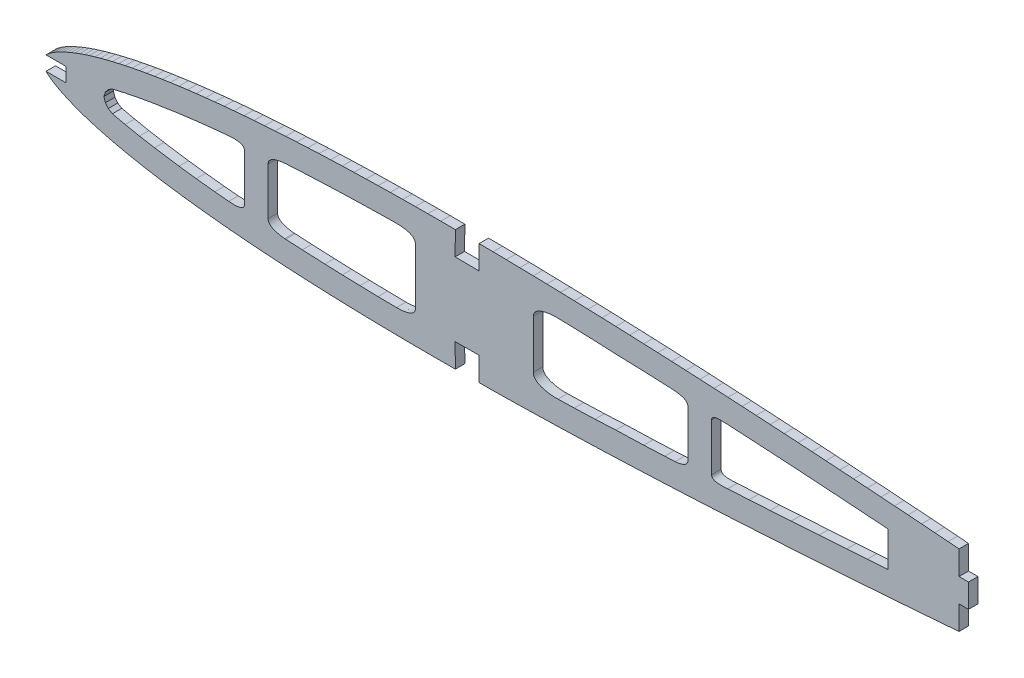
SolidWorks part; units mm, degrees
ref_plane "前视基准面" through (0, 0, 0) normal (0, 0, 1) x (1, 0, 0)
ref_plane "上视基准面" through (0, 0, 0) normal (0, 1, 0) x (1, 0, 0)
ref_plane "右视基准面" through (0, 0, 0) normal (1, 0, 0) x (0, 0, -1)
sketch "Model" plane through (0, 0, 0) normal (0, 0, 1) x (1, 0, 0)
  line L0 (191.5152, 23.6015) -> (189.1892, 23.7857)
  line L1 (189.1892, 23.7857) -> (186.3982, 24.0037)
  line L2 (186.3982, 24.0037) -> (183.6072, 24.2187)
  line L3 (183.6072, 24.2187) -> (180.7582, 24.4357)
  line L4 (180.7582, 24.4357) -> (177.9092, 24.6477)
  line L5 (177.9092, 24.6477) -> (175.0602, 24.8567)
  line L6 (175.0602, 24.8567) -> (172.1632, 25.0647)
  line L7 (172.1632, 25.0647) -> (169.2682, 25.2687)
  line L8 (169.2682, 25.2687) -> (166.3712, 25.4687)
  line L9 (166.3712, 25.4687) -> (163.4412, 25.6677)
  line L10 (163.4412, 25.6677) -> (160.5112, 25.8627)
  line L11 (160.5112, 25.8627) -> (157.5802, 26.0527)
  line L12 (157.5802, 26.0527) -> (154.6252, 26.2367)
  line L13 (154.6252, 26.2367) -> (151.6712, 26.4157)
  line L14 (151.6712, 26.4157) -> (148.7162, 26.5907)
  line L15 (148.7162, 26.5907) -> (145.7502, 26.7647)
  line L16 (145.7502, 26.7647) -> (142.7862, 26.9337)
  line L17 (142.7862, 26.9337) -> (139.8202, 27.0977)
  line L18 (139.8202, 27.0977) -> (136.8552, 27.2557)
  line L19 (136.8552, 27.2557) -> (133.8902, 27.4057)
  line L20 (133.8902, 27.4057) -> (130.9242, 27.5487)
  line L21 (130.9242, 27.5487) -> (127.9702, 27.6847)
  line L22 (127.9702, 27.6847) -> (125.0152, 27.8137)
  line L23 (125.0152, 27.8137) -> (122.0602, 27.9367)
  line L24 (122.0602, 27.9367) -> (119.1302, 28.0527)
  line L25 (119.1302, 28.0527) -> (116.2002, 28.1617)
  line L26 (116.2002, 28.1617) -> (113.2692, 28.2627)
  line L27 (113.2692, 28.2627) -> (110.3732, 28.3557)
  line L28 (110.3732, 28.3557) -> (107.4772, 28.4407)
  line L29 (107.4772, 28.4407) -> (104.5802, 28.5177)
  line L30 (104.5802, 28.5177) -> (101.7312, 28.5867)
  line L31 (101.7312, 28.5867) -> (98.8832, 28.6477)
  line L32 (98.8832, 28.6477) -> (96.0332, 28.6997)
  line L33 (96.0332, 28.6997) -> (93.2422, 28.7417)
  line L34 (93.2422, 28.7417) -> (90.2887, 28.7567)
  line L35 (12.9542, 18.3227) -> (15.6532, 18.9327)
  line L36 (15.6532, 18.9327) -> (18.6702, 19.5337)
  line L37 (18.6702, 19.5337) -> (21.8492, 20.0927)
  line L38 (21.8492, 20.0927) -> (27.0022, 20.8667)
  line L39 (27.0022, 20.8667) -> (30.6412, 21.3307)
  line L40 (30.6412, 21.3307) -> (34.5652, 21.7657)
  line L41 (34.5652, 21.7657) -> (37.7693, 22.0681)
  line L42 (49.5012, 22.9567) -> (53.0172, 23.1467)
  line L43 (53.0172, 23.1467) -> (57.193, 23.3345)
  line L44 (59.6022, 23.4284) -> (61.4422, 23.4967)
  line L45 (61.4422, 23.4967) -> (65.1737, 23.6052)
  line L46 (65.1737, 23.6052) -> (69.0032, 23.6947)
  line L47 (69.0032, 23.6947) -> (72.3897, 23.7484)
  line L48 (72.8792, 8.3632) -> (69.0032, 8.4247)
  line L49 (69.0032, 8.4247) -> (65.1737, 8.5142)
  line L50 (65.1737, 8.5142) -> (61.4422, 8.6227)
  line L51 (61.4422, 8.6227) -> (57.7622, 8.7592)
  line L52 (57.7622, 8.7592) -> (53.0172, 8.9727)
  line L53 (53.0172, 8.9727) -> (49.5012, 9.1627)
  line L54 (49.5012, 9.1627) -> (49.2998, 9.1756)
  line L55 (37.4946, 10.0771) -> (34.5652, 10.3537)
  line L56 (34.5652, 10.3537) -> (30.6412, 10.7887)
  line L57 (30.6412, 10.7887) -> (27.0022, 11.2527)
  line L58 (27.0022, 11.2527) -> (21.8492, 12.0267)
  line L59 (21.8492, 12.0267) -> (18.6702, 12.5857)
  line L60 (18.6702, 12.5857) -> (15.6532, 13.1867)
  line L61 (15.6532, 13.1867) -> (12.9542, 13.7967)
  line L62 (12.9542, 18.3227) -> (12.0865, 17.8016)
  line L63 (12.0865, 17.8016) -> (11.4898, 17.0319)
  line L64 (11.4898, 17.0319) -> (11.1665, 16.0597)
  line L65 (12.9542, 13.7967) -> (12.0865, 14.3178)
  line L66 (12.0865, 14.3178) -> (11.4898, 15.0874)
  line L67 (11.4898, 15.0874) -> (11.1665, 16.0597)
  line L68 (106.8793, 23.455) -> (110.3732, 23.3557)
  line L69 (110.3732, 23.3557) -> (113.5776, 23.2502)
  line L70 (116.1585, 23.1417) -> (119.1302, 22.9947)
  line L71 (119.1302, 22.9947) -> (125.0152, 22.8137)
  line L72 (125.0152, 22.8137) -> (129.4472, 22.6167)
  line L73 (129.4472, 22.6167) -> (131.1657, 22.5337)
  line L74 (142.5984, 21.9418) -> (147.2332, 21.6777)
  line L75 (147.2332, 21.6777) -> (151.6712, 21.4157)
  line L76 (151.6712, 21.4157) -> (156.1027, 21.1447)
  line L77 (156.1027, 21.1447) -> (161.9762, 20.7652)
  line L78 (161.9762, 20.7652) -> (167.8197, 20.3687)
  line L79 (167.8197, 20.3687) -> (172.1632, 20.0647)
  line L80 (172.1632, 20.0647) -> (176.4847, 19.7522)
  line L81 (176.4847, 12.3672) -> (172.1632, 12.0547)
  line L82 (172.1632, 12.0547) -> (167.8197, 11.7507)
  line L83 (167.8197, 11.7507) -> (161.9762, 11.3542)
  line L84 (161.9762, 11.3542) -> (156.1027, 10.9747)
  line L85 (156.1027, 10.9747) -> (151.6712, 10.7037)
  line L86 (151.6712, 10.7037) -> (147.2332, 10.4417)
  line L87 (147.2332, 10.4417) -> (142.7123, 10.184)
  line L88 (131.6382, 9.6084) -> (129.4472, 9.5027)
  line L89 (129.4472, 9.5027) -> (125.0152, 9.3057)
  line L90 (125.0152, 9.3057) -> (119.1302, 9.1247)
  line L91 (119.1302, 9.1247) -> (114.7347, 8.9072)
  line L92 (114.7347, 8.9072) -> (110.3732, 8.7637)
  line L93 (110.3732, 8.7637) -> (106.9137, 8.6653)
  line L94 (101.7303, 10.9658) -> (101.7303, 21.1535)
  line L95 (76.8452, 22.0156) -> (76.8452, 10.1038)
  line L96 (45.7904, 21.0597) -> (45.7904, 11.0597)
  line L97 (40.7904, 11.0597) -> (40.7904, 21.0597)
  line L98 (139.3252, 21.0597) -> (139.3252, 11.0597)
  line L99 (134.3252, 11.0597) -> (134.3252, 21.0597)
  line L100 (193.5152, 16.0597) -> (193.5152, 18.5597)
  line L101 (193.5152, 16.0597) -> (193.5152, 13.5597)
  line L102 (193.5152, 18.5597) -> (191.5152, 18.5597)
  line L103 (193.5152, 13.5597) -> (191.5152, 13.5597)
  line L104 (191.5152, 18.5597) -> (191.5152, 23.6015)
  line L105 (191.5152, 13.5597) -> (191.5152, 8.5188)
  line L106 (176.4847, 19.7522) -> (176.4847, 12.3672)
  line L107 (113.5776, 23.2502) -> (116.1585, 23.1417)
  line L108 (57.193, 23.3345) -> (59.6022, 23.4284)
  line L109 (85.2897, 28.8017) -> (82.2132, 28.8177)
  line L110 (82.2132, 28.8177) -> (79.4892, 28.8127)
  line L111 (79.4892, 28.8127) -> (76.8452, 28.7987)
  line L112 (76.8452, 28.7987) -> (74.2012, 28.7737)
  line L113 (74.2012, 28.7737) -> (71.5572, 28.7387)
  line L114 (71.5572, 28.7387) -> (69.0032, 28.6947)
  line L115 (69.0032, 28.6947) -> (66.4502, 28.6387)
  line L116 (66.4502, 28.6387) -> (63.8972, 28.5717)
  line L117 (63.8972, 28.5717) -> (61.4422, 28.4967)
  line L118 (61.4422, 28.4967) -> (58.9892, 28.4097)
  line L119 (58.9892, 28.4097) -> (56.5352, 28.3107)
  line L120 (56.5352, 28.3107) -> (54.1892, 28.2057)
  line L121 (54.1892, 28.2057) -> (51.8452, 28.0877)
  line L122 (51.8452, 28.0877) -> (49.5012, 27.9567)
  line L123 (49.5012, 27.9567) -> (47.2742, 27.8197)
  line L124 (47.2742, 27.8197) -> (45.0492, 27.6697)
  line L125 (45.0492, 27.6697) -> (42.8242, 27.5067)
  line L126 (42.8242, 27.5067) -> (40.7252, 27.3387)
  line L127 (40.7252, 27.3387) -> (38.6272, 27.1577)
  line L128 (38.6272, 27.1577) -> (36.5302, 26.9617)
  line L129 (36.5302, 26.9617) -> (34.5652, 26.7657)
  line L130 (34.5652, 26.7657) -> (32.6032, 26.5557)
  line L131 (32.6032, 26.5557) -> (30.6412, 26.3307)
  line L132 (30.6412, 26.3307) -> (28.8212, 26.1057)
  line L133 (28.8212, 26.1057) -> (27.0022, 25.8667)
  line L134 (27.0022, 25.8667) -> (25.1862, 25.6107)
  line L135 (25.1862, 25.6107) -> (23.5162, 25.3597)
  line L136 (23.5162, 25.3597) -> (21.8492, 25.0927)
  line L137 (21.8492, 25.0927) -> (20.1842, 24.8087)
  line L138 (20.1842, 24.8087) -> (18.6702, 24.5337)
  line L139 (18.6702, 24.5337) -> (17.1602, 24.2427)
  line L140 (17.1602, 24.2427) -> (15.6532, 23.9327)
  line L141 (15.6532, 23.9327) -> (14.3012, 23.6367)
  line L142 (14.3012, 23.6367) -> (12.9542, 23.3227)
  line L143 (12.9542, 23.3227) -> (11.6122, 22.9887)
  line L144 (11.6122, 22.9887) -> (10.4272, 22.6767)
  line L145 (10.4272, 22.6767) -> (9.2482, 22.3467)
  line L146 (9.2482, 22.3467) -> (8.0752, 21.9947)
  line L147 (8.0752, 21.9947) -> (7.0622, 21.6687)
  line L148 (7.0622, 21.6687) -> (6.0562, 21.3227)
  line L149 (6.0562, 21.3227) -> (5.0602, 20.9517)
  line L150 (5.0602, 20.9517) -> (4.2242, 20.6167)
  line L151 (4.2242, 20.6167) -> (3.3962, 20.2617)
  line L152 (3.3962, 20.2617) -> (2.5772, 19.8857)
  line L153 (2.5772, 19.8857) -> (1.9182, 19.5637)
  line L154 (1.9182, 19.5637) -> (1.2692, 19.2207)
  line L155 (1.2692, 19.2207) -> (0.6362, 18.8487)
  line L156 (0.6362, 18.8487) -> (0.1522, 18.5327)
  line L157 (0.1522, 18.5327) -> (-0.3138, 18.1927)
  line L158 (-0.3138, 18.1927) -> (-0.7578, 17.8257)
  line L159 (-0.7578, 17.8257) -> (-1.0424, 17.5597)
  line L160 (90.2887, 3.3637) -> (93.2422, 3.3787)
  line L161 (93.2422, 3.3787) -> (96.0332, 3.4207)
  line L162 (96.0332, 3.4207) -> (98.8832, 3.4727)
  line L163 (98.8832, 3.4727) -> (101.7312, 3.5337)
  line L164 (101.7312, 3.5337) -> (104.5802, 3.6027)
  line L165 (104.5802, 3.6027) -> (107.4772, 3.6797)
  line L166 (107.4772, 3.6797) -> (110.3732, 3.7647)
  line L167 (110.3732, 3.7647) -> (113.2692, 3.8577)
  line L168 (113.2692, 3.8577) -> (116.2002, 3.9587)
  line L169 (116.2002, 3.9587) -> (119.1302, 4.0677)
  line L170 (119.1302, 4.0677) -> (122.0602, 4.1837)
  line L171 (122.0602, 4.1837) -> (125.0152, 4.3067)
  line L172 (125.0152, 4.3067) -> (127.9702, 4.4357)
  line L173 (127.9702, 4.4357) -> (130.9242, 4.5717)
  line L174 (130.9242, 4.5717) -> (133.8902, 4.7147)
  line L175 (133.8902, 4.7147) -> (136.8552, 4.8647)
  line L176 (136.8552, 4.8647) -> (139.8202, 5.0217)
  line L177 (139.8202, 5.0217) -> (142.7862, 5.1867)
  line L178 (142.7862, 5.1867) -> (145.7502, 5.3557)
  line L179 (145.7502, 5.3557) -> (148.7162, 5.5297)
  line L180 (148.7162, 5.5297) -> (151.6712, 5.7047)
  line L181 (151.6712, 5.7047) -> (154.6252, 5.8837)
  line L182 (154.6252, 5.8837) -> (157.5802, 6.0677)
  line L183 (157.5802, 6.0677) -> (160.5112, 6.2567)
  line L184 (160.5112, 6.2567) -> (163.4412, 6.4517)
  line L185 (163.4412, 6.4517) -> (166.3712, 6.6517)
  line L186 (166.3712, 6.6517) -> (169.2682, 6.8517)
  line L187 (169.2682, 6.8517) -> (172.1632, 7.0557)
  line L188 (172.1632, 7.0557) -> (175.0602, 7.2637)
  line L189 (175.0602, 7.2637) -> (177.9092, 7.4727)
  line L190 (177.9092, 7.4727) -> (180.7582, 7.6847)
  line L191 (180.7582, 7.6847) -> (183.6072, 7.9017)
  line L192 (183.6072, 7.9017) -> (186.3982, 8.1167)
  line L193 (186.3982, 8.1167) -> (189.1892, 8.3347)
  line L194 (189.1892, 8.3347) -> (191.5152, 8.5188)
  line L195 (-1.0424, 17.5597) -> (3.1252, 17.5597)
  line L196 (3.1252, 17.5597) -> (3.1252, 14.5597)
  line L197 (3.1252, 14.5597) -> (-1.0413, 14.5597)
  line L198 (-1.0413, 14.5597) -> (-0.7578, 14.2947)
  line L199 (-0.7578, 14.2947) -> (-0.3138, 13.9277)
  line L200 (-0.3138, 13.9277) -> (0.1522, 13.5877)
  line L201 (0.1522, 13.5877) -> (0.6362, 13.2717)
  line L202 (0.6362, 13.2717) -> (1.2692, 12.8997)
  line L203 (1.2692, 12.8997) -> (1.9182, 12.5567)
  line L204 (1.9182, 12.5567) -> (2.5772, 12.2347)
  line L205 (2.5772, 12.2347) -> (3.3962, 11.8587)
  line L206 (3.3962, 11.8587) -> (4.2242, 11.5037)
  line L207 (4.2242, 11.5037) -> (5.0602, 11.1687)
  line L208 (5.0602, 11.1687) -> (6.0562, 10.7977)
  line L209 (6.0562, 10.7977) -> (7.0622, 10.4517)
  line L210 (7.0622, 10.4517) -> (8.0752, 10.1257)
  line L211 (8.0752, 10.1257) -> (9.2482, 9.7737)
  line L212 (9.2482, 9.7737) -> (10.4272, 9.4437)
  line L213 (10.4272, 9.4437) -> (11.6122, 9.1317)
  line L214 (11.6122, 9.1317) -> (12.9542, 8.7977)
  line L215 (12.9542, 8.7977) -> (14.3012, 8.4837)
  line L216 (14.3012, 8.4837) -> (15.6532, 8.1877)
  line L217 (15.6532, 8.1877) -> (17.1602, 7.8777)
  line L218 (17.1602, 7.8777) -> (18.6702, 7.5867)
  line L219 (18.6702, 7.5867) -> (20.1842, 7.3117)
  line L220 (20.1842, 7.3117) -> (21.8492, 7.0277)
  line L221 (21.8492, 7.0277) -> (23.5162, 6.7607)
  line L222 (23.5162, 6.7607) -> (25.1862, 6.5097)
  line L223 (25.1862, 6.5097) -> (27.0022, 6.2537)
  line L224 (27.0022, 6.2537) -> (28.8212, 6.0147)
  line L225 (28.8212, 6.0147) -> (30.6412, 5.7897)
  line L226 (30.6412, 5.7897) -> (32.6032, 5.5647)
  line L227 (32.6032, 5.5647) -> (34.5652, 5.3547)
  line L228 (34.5652, 5.3547) -> (36.5302, 5.1577)
  line L229 (36.5302, 5.1577) -> (38.6272, 4.9627)
  line L230 (38.6272, 4.9627) -> (40.7252, 4.7817)
  line L231 (40.7252, 4.7817) -> (42.8242, 4.6137)
  line L232 (42.8242, 4.6137) -> (45.0492, 4.4507)
  line L233 (45.0492, 4.4507) -> (47.2742, 4.3007)
  line L234 (47.2742, 4.3007) -> (49.5012, 4.1637)
  line L235 (49.5012, 4.1637) -> (51.8452, 4.0327)
  line L236 (51.8452, 4.0327) -> (54.1892, 3.9147)
  line L237 (54.1892, 3.9147) -> (56.5352, 3.8097)
  line L238 (56.5352, 3.8097) -> (58.9892, 3.7107)
  line L239 (58.9892, 3.7107) -> (61.4422, 3.6237)
  line L240 (61.4422, 3.6237) -> (63.8972, 3.5487)
  line L241 (63.8972, 3.5487) -> (66.4502, 3.4817)
  line L242 (66.4502, 3.4817) -> (69.0032, 3.4257)
  line L243 (69.0032, 3.4257) -> (71.5572, 3.3817)
  line L244 (71.5572, 3.3817) -> (74.2012, 3.3467)
  line L245 (74.2012, 3.3467) -> (76.8452, 3.3217)
  line L246 (76.8452, 3.3217) -> (79.4892, 3.3077)
  line L247 (79.4892, 3.3077) -> (82.2132, 3.3027)
  line L248 (82.2132, 3.3027) -> (85.2897, 3.3177)
  line L249 (85.2897, 28.8017) -> (85.2437, 23.8027)
  line L250 (85.2437, 23.8027) -> (90.2427, 23.7567)
  line L251 (90.2427, 23.7567) -> (90.2887, 28.7567)
  line L252 (85.2897, 3.3177) -> (85.2437, 8.3177)
  line L253 (85.2437, 8.3177) -> (90.2437, 8.3637)
  line L254 (90.2437, 8.3637) -> (90.2887, 3.3637)
  spline S0 degree 3 poles (106.8793, 23.455) (105.0001, 23.5084) (101.7303, 23.0334) (101.7303, 21.1535) knots 0 0 0 0 5.639881 5.639881 5.639881 5.639881
  spline S1 degree 3 poles (101.7303, 10.9658) (101.7303, 9.0755) (105.0241, 8.6116) (106.9137, 8.6653) knots 0 0 0 0 5.670909 5.670909 5.670909 5.670909
  spline S2 degree 3 poles (72.3897, 23.7484) (73.983, 23.7737) (76.8452, 23.6091) (76.8452, 22.0156) knots 0 0 0 0 4.780561 4.780561 4.780561 4.780561
  spline S3 degree 3 poles (72.8792, 8.3632) (74.3227, 8.3403) (76.8452, 8.66) (76.8452, 10.1038) knots 0 0 0 0 4.331148 4.331148 4.331148 4.331148
  spline S4 degree 3 poles (37.7693, 22.0681) (38.8262, 22.1679) (40.7904, 22.1213) (40.7904, 21.0597) knots 0 0 0 0 3.184993 3.184993 3.184993 3.184993
  spline S5 degree 3 poles (49.5012, 22.9567) (48.114, 22.8817) (45.7904, 22.4488) (45.7904, 21.0597) knots 0 0 0 0 4.167565 4.167565 4.167565 4.167565
  spline S6 degree 3 poles (37.4946, 10.0771) (38.6359, 9.9694) (40.7904, 9.9133) (40.7904, 11.0597) knots 0 0 0 0 3.43911 3.43911 3.43911 3.43911
  spline S7 degree 3 poles (49.2998, 9.1756) (47.9749, 9.2611) (45.7904, 9.7319) (45.7904, 11.0597) knots 0 0 0 0 3.983183 3.983183 3.983183 3.983183
  spline S8 degree 3 poles (131.1657, 22.5337) (132.3265, 22.4777) (134.3252, 22.2218) (134.3252, 21.0597) knots 0 0 0 0 3.486453 3.486453 3.486453 3.486453
  spline S9 degree 3 poles (131.6382, 9.6084) (132.655, 9.6575) (134.3252, 10.0417) (134.3252, 11.0597) knots 0 0 0 0 3.053828 3.053828 3.053828 3.053828
  spline S10 degree 3 poles (139.3252, 21.0597) (139.3252, 22.1897) (141.4702, 22.0061) (142.5984, 21.9418) knots 0 0 0 0 3.389995 3.389995 3.389995 3.389995
  spline S11 degree 3 poles (139.3252, 11.0597) (139.3252, 9.8935) (141.5481, 10.1176) (142.7123, 10.184) knots 0 0 0 0 3.498515 3.498515 3.498515 3.498515
extrude "凸台-拉伸1" add sketch "Model" along normal blind 2
